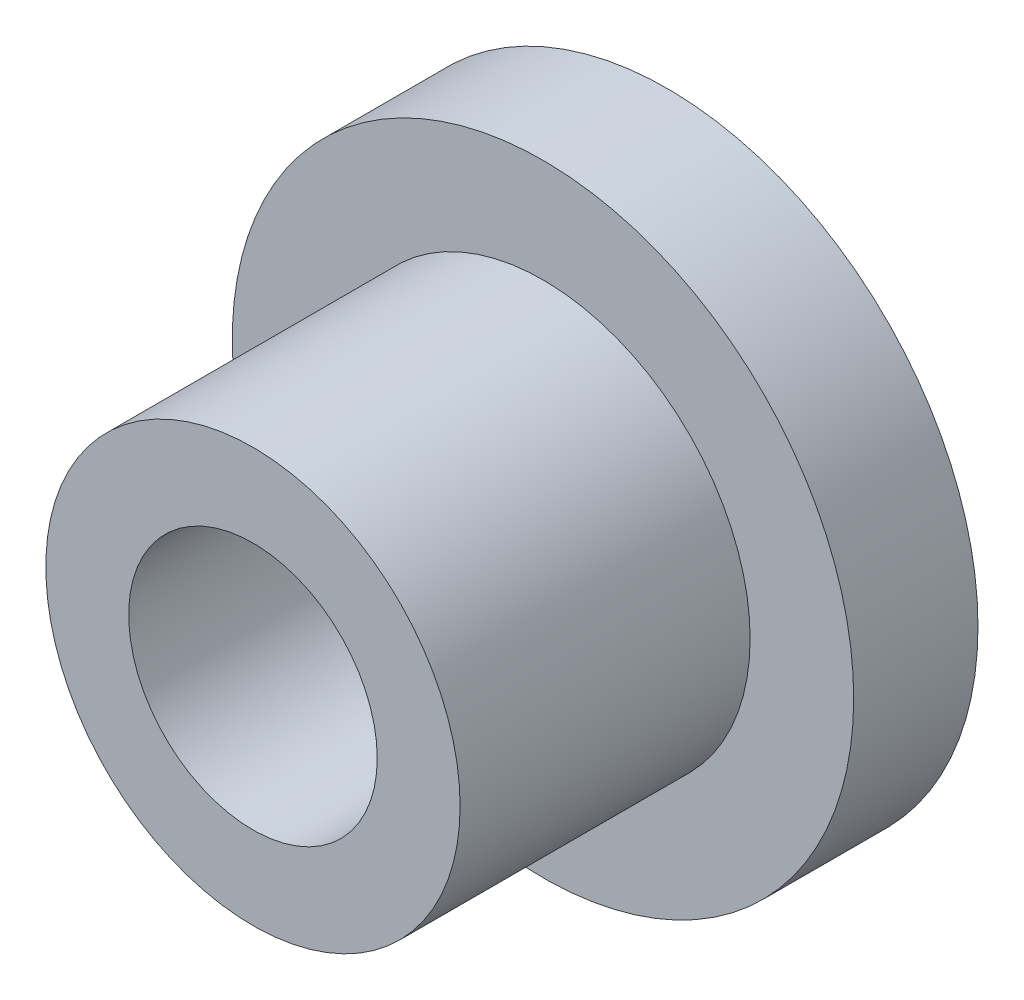
SolidWorks part; units mm, degrees
ref_plane "Ön Düzlem" through (0, 0, 0) normal (0, 0, 1) x (1, 0, 0)
ref_plane "Üst Düzlem" through (0, 0, 0) normal (0, 1, 0) x (1, 0, 0)
ref_plane "Sağ Düzlem" through (0, 0, 0) normal (1, 0, 0) x (0, 0, -1)
sketch "Sketch1" plane through (0, 0, 0) normal (0, 0, 1) x (1, 0, 0)
  circle A0 centre (0, 0) radius 15
  dimension "D1" = 30
extrude "Boss-Extrude1" add sketch "Sketch1" along normal blind 6
sketch "Sketch2" plane through (0, 0, 6) normal (0, 0, 1) x (1, 0, 0)
  circle A0 centre (0, 0) radius 10
  dimension "D1" = 20
extrude "Boss-Extrude2" add sketch "Sketch2" along normal blind 14
sketch "Sketch3" plane through (0, 0, 20) normal (0, 0, 1) x (1, 0, 0)
  circle A0 centre (0, 0) radius 6
  dimension "D1" = 12
extrude "Cut-Extrude1" cut sketch "Sketch3" against normal through all
